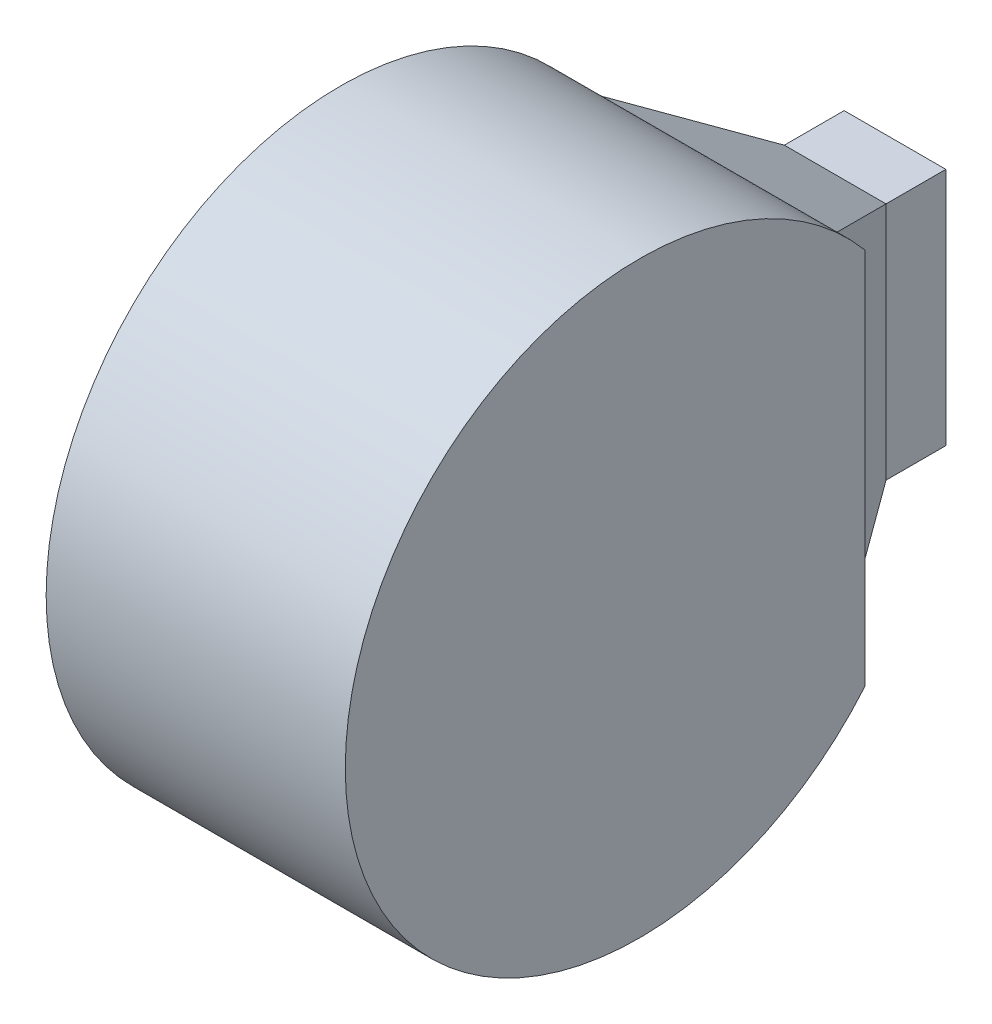
SolidWorks part; units mm, degrees
ref_plane "前视基准面" through (0, 0, 0) normal (0, 0, 1) x (1, 0, 0)
ref_plane "上视基准面" through (0, 0, 0) normal (0, 1, 0) x (1, 0, 0)
ref_plane "右视基准面" through (0, 0, 0) normal (1, 0, 0) x (0, 0, -1)
sketch "草图1" plane through (0, 0, 0) normal (0, 0, 1) x (1, 0, 0)
  line L1 (-8.5, 20) -> (8.5, 20)
  line L2 (-8.5, 20) -> (-8.5, -20)
  line L3 (-8.5, -20) -> (8.5, -20)
  line L4 (8.5, 20) -> (8.5, -20)
  line L5 (-8.5, 20) -> (8.5, -20) construction
  line L6 (-8.5, -20) -> (8.5, 20) construction
  point P0 (0, 0)
  dimension "D1" = 40
  dimension "D2" = 17
extrude "凸台-拉伸1" add sketch "草图1" along normal blind 10
sketch "草图2" plane through (0, 0, 10) normal (0, 0, 1) x (1, 0, 0)
  line L4 (8.5, -20) -> (8.5, 20)
  line L5 (8.5, 20) -> (-8.5, 20)
  line L6 (-8.5, 20) -> (-8.5, -20)
  line L7 (-8.5, -20) -> (8.5, -20)
  line L8 (8.5, -20) -> (8.5, 20)
  line L9 (8.5, 20) -> (-8.5, 20)
  line L10 (-8.5, 20) -> (-8.5, -20)
  line L11 (-8.5, -20) -> (8.5, -20)
  dimension "D1" = 0
extrude "凸台-拉伸2" add sketch "草图2" along normal blind 20 draft 30
sketch "草图3" plane through (0, 0, 0) normal (1, 0, 0) x (0, 0, -1)
  line L0 (-30, 31.547) -> (-30, -31.547)
  arc A0 (-30, 31.547) -> (-30, -31.547) centre (-67.7158, 0) ccw
extrude "凸台-拉伸3" add sketch "草图3" along normal mid plane 50
